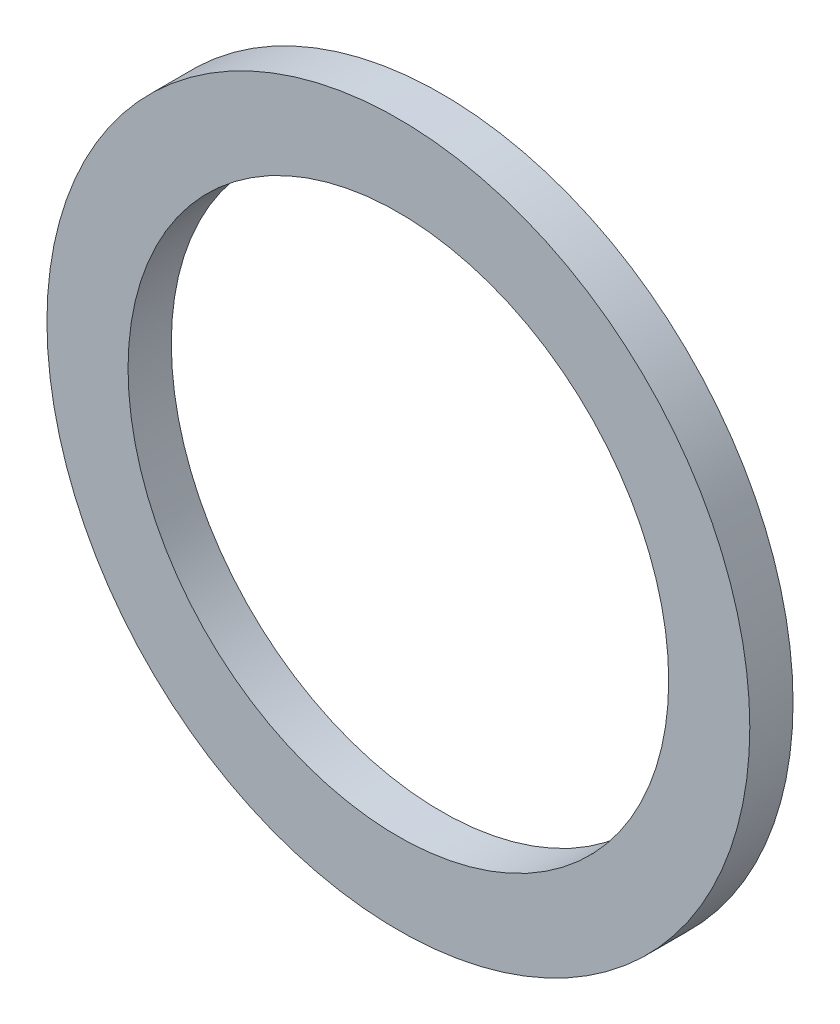
SolidWorks part; units mm, degrees
ref_plane "Plan de face" through (0, 0, 0) normal (0, 0, 1) x (1, 0, 0)
ref_plane "Plan de dessus" through (0, 0, 0) normal (0, 1, 0) x (1, 0, 0)
ref_plane "Plan de droite" through (0, 0, 0) normal (1, 0, 0) x (0, 0, -1)
sketch "Esquisse1" plane through (0, 0, 0) normal (0, 0, 1) x (1, 0, 0)
  circle A0 centre (0, 0) radius 5
  circle A1 centre (0, 0) radius 6.5
  dimension "D1" = 10
  dimension "D2" = 13
extrude "Boss.-Extru.1" add sketch "Esquisse1" along normal blind 0.8
